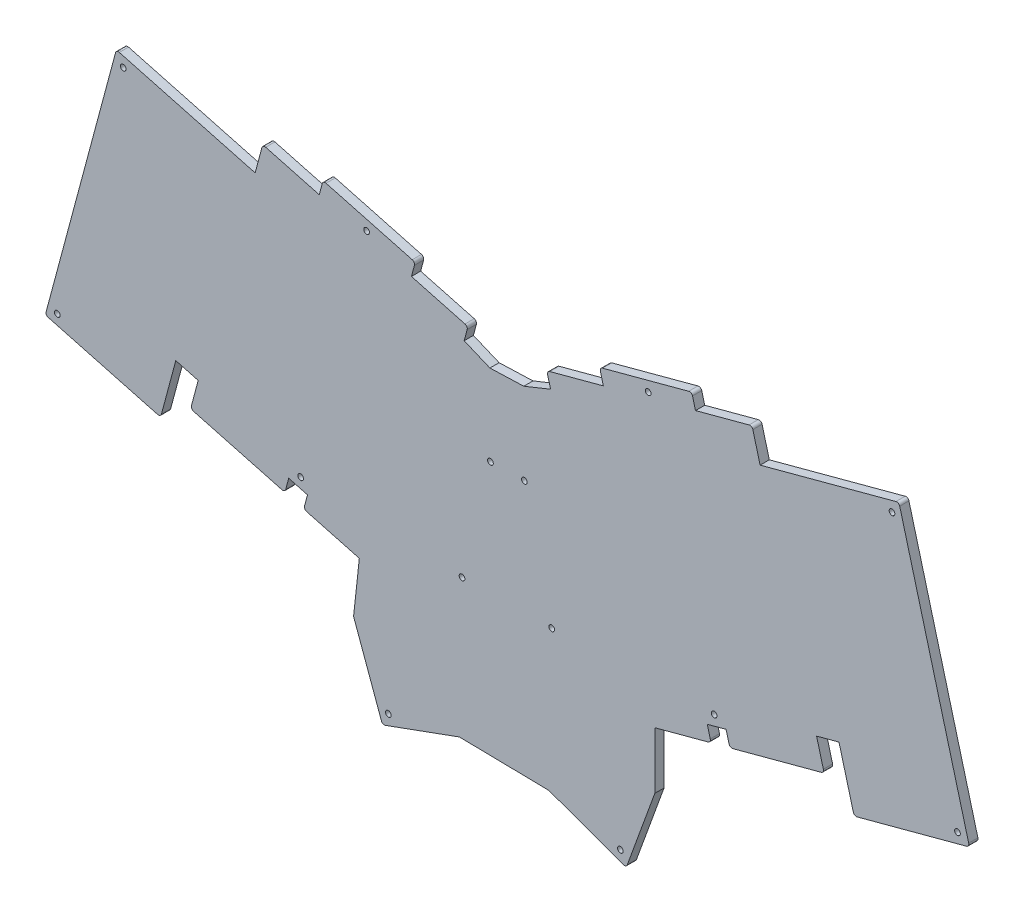
SolidWorks part; units mm, degrees
ref_plane "Front Plane" through (0, 0, 0) normal (0, 0, 1) x (1, 0, 0)
ref_plane "Top Plane" through (0, 0, 0) normal (0, 1, 0) x (1, 0, 0)
ref_plane "Right Plane" through (0, 0, 0) normal (1, 0, 0) x (0, 0, -1)
sketch "Model" plane through (0, 0, 0) normal (0, 0, 1) x (1, 0, 0)
  line L0 (282.165, 226.202) -> (288.4436, 227.8841) construction
  line L1 (267.373, 281.405) -> (273.6516, 283.0871) construction
  line L2 (195.392, 284.0785) -> (194.5766, 287.1211) construction
  line L3 (100.681, 283.685) -> (101.4961, 286.7277) construction
  line L4 (168.22, 168.742) -> (181.234, 164.006) construction
  line L5 (181.234, 164.006) -> (185.972, 177.021) construction
  line L6 (185.972, 177.021) -> (172.956, 181.758) construction
  line L7 (172.956, 181.758) -> (168.22, 168.742) construction
  line L8 (132.176, 184.752) -> (133.281, 181.717) construction
  line L9 (133.281, 181.717) -> (131.706, 181.144) construction
  line L10 (131.706, 181.144) -> (130.099, 185.56) construction
  line L11 (130.099, 185.56) -> (117.085, 180.823) construction
  line L12 (117.085, 180.823) -> (118.692, 176.407) construction
  line L13 (118.692, 176.407) -> (117.118, 175.834) construction
  line L14 (117.118, 175.834) -> (116.013, 178.869) construction
  line L15 (116.013, 178.869) -> (109.812, 176.612) construction
  line L16 (109.812, 176.612) -> (110.917, 173.576) construction
  line L17 (110.917, 173.576) -> (110.141, 173.294) construction
  line L18 (110.141, 173.294) -> (111.048, 170.804) construction
  line L19 (111.048, 170.804) -> (111.822, 171.086) construction
  line L20 (111.822, 171.086) -> (113.968, 165.194) construction
  line L21 (113.968, 165.194) -> (115.588, 165.784) construction
  line L22 (115.588, 165.784) -> (115.999, 164.656) construction
  line L23 (115.999, 164.656) -> (118.959, 165.734) construction
  line L24 (118.959, 165.734) -> (118.549, 166.861) construction
  line L25 (118.549, 166.861) -> (120.169, 167.452) construction
  line L26 (120.169, 167.452) -> (118.641, 171.651) construction
  line L27 (118.641, 171.651) -> (120.215, 172.224) construction
  line L28 (120.215, 172.224) -> (121.821, 167.809) construction
  line L29 (121.821, 167.809) -> (134.837, 172.545) construction
  line L30 (134.837, 172.545) -> (133.23, 176.962) construction
  line L31 (133.23, 176.962) -> (134.804, 177.535) construction
  line L32 (134.804, 177.535) -> (136.332, 173.335) construction
  line L33 (136.332, 173.335) -> (137.953, 173.925) construction
  line L34 (137.953, 173.925) -> (138.363, 172.796) construction
  line L35 (138.363, 172.796) -> (141.323, 173.874) construction
  line L36 (141.323, 173.874) -> (140.913, 175.001) construction
  line L37 (140.913, 175.001) -> (142.533, 175.592) construction
  line L38 (142.533, 175.592) -> (140.389, 181.483) construction
  line L39 (140.389, 181.483) -> (141.165, 181.766) construction
  line L40 (141.165, 181.766) -> (140.258, 184.256) construction
  line L41 (140.258, 184.256) -> (139.484, 183.974) construction
  line L42 (139.484, 183.974) -> (138.378, 187.009) construction
  line L43 (138.378, 187.009) -> (132.176, 184.752) construction
  line L44 (150.319, 175.258) -> (163.333, 170.521) construction
  line L45 (163.333, 170.521) -> (168.071, 183.535) construction
  line L46 (168.071, 183.535) -> (155.055, 188.273) construction
  line L47 (155.055, 188.273) -> (150.319, 175.258) construction
  line L48 (109.952, 197.835) -> (123.33, 194.251) construction
  line L49 (123.33, 194.251) -> (126.916, 207.629) construction
  line L50 (126.916, 207.629) -> (113.537, 211.213) construction
  line L51 (113.537, 211.213) -> (109.952, 197.835) construction
  line L52 (169.157, 208.022) -> (172.741, 194.644) construction
  line L53 (172.741, 194.644) -> (186.119, 198.228) construction
  line L54 (186.119, 198.228) -> (182.535, 211.607) construction
  line L55 (182.535, 211.607) -> (169.157, 208.022) construction
  line L56 (92.7848, 207.366) -> (106.163, 203.781) construction
  line L57 (106.163, 203.781) -> (109.747, 217.159) construction
  line L58 (109.747, 217.159) -> (96.369, 220.744) construction
  line L59 (96.369, 220.744) -> (92.7848, 207.366) construction
  line L60 (186.326, 217.552) -> (189.91, 204.174) construction
  line L61 (189.91, 204.174) -> (203.288, 207.759) construction
  line L62 (203.288, 207.759) -> (199.704, 221.137) construction
  line L63 (199.704, 221.137) -> (186.326, 217.552) construction
  line L64 (114.883, 216.236) -> (128.261, 212.652) construction
  line L65 (128.261, 212.652) -> (131.845, 226.03) construction
  line L66 (131.845, 226.03) -> (118.467, 229.614) construction
  line L67 (118.467, 229.614) -> (114.883, 216.236) construction
  line L68 (164.226, 226.423) -> (167.812, 213.045) construction
  line L69 (167.812, 213.045) -> (181.19, 216.629) construction
  line L70 (181.19, 216.629) -> (177.604, 230.007) construction
  line L71 (177.604, 230.007) -> (164.226, 226.423) construction
  line L72 (75.6158, 216.896) -> (88.9938, 213.312) construction
  line L73 (88.9938, 213.312) -> (92.5781, 226.69) construction
  line L74 (92.5781, 226.69) -> (79.2, 230.274) construction
  line L75 (79.2, 230.274) -> (75.6158, 216.896) construction
  line L76 (55.9827, 217.227) -> (69.3607, 213.643) construction
  line L77 (69.3607, 213.643) -> (72.9449, 227.021) construction
  line L78 (72.9449, 227.021) -> (59.5672, 230.605) construction
  line L79 (59.5672, 230.605) -> (55.9827, 217.227) construction
  line L80 (203.494, 227.083) -> (207.078, 213.705) construction
  line L81 (207.078, 213.705) -> (220.457, 217.29) construction
  line L82 (220.457, 217.29) -> (216.872, 230.668) construction
  line L83 (216.872, 230.668) -> (203.494, 227.083) construction
  line L84 (223.128, 227.414) -> (226.712, 214.036) construction
  line L85 (226.712, 214.036) -> (240.09, 217.62) construction
  line L86 (240.09, 217.62) -> (236.506, 230.998) construction
  line L87 (236.506, 230.998) -> (223.128, 227.414) construction
  line L88 (12.1157, 219.121) -> (25.4937, 215.536) construction
  line L89 (25.4937, 215.536) -> (29.078, 228.914) construction
  line L90 (29.078, 228.914) -> (15.7, 232.499) construction
  line L91 (15.7, 232.499) -> (12.1157, 219.121) construction
  line L92 (266.995, 229.307) -> (270.579, 215.929) construction
  line L93 (270.579, 215.929) -> (283.957, 219.513) construction
  line L94 (283.957, 219.513) -> (280.373, 232.891) construction
  line L95 (280.373, 232.891) -> (266.995, 229.307) construction
  line L96 (97.7138, 225.767) -> (111.092, 222.183) construction
  line L97 (111.092, 222.183) -> (114.677, 235.56) construction
  line L98 (114.677, 235.56) -> (101.299, 239.145) construction
  line L99 (101.299, 239.145) -> (97.7138, 225.767) construction
  line L100 (181.394, 235.953) -> (184.98, 222.575) construction
  line L101 (184.98, 222.575) -> (198.357, 226.159) construction
  line L102 (198.357, 226.159) -> (194.773, 239.538) construction
  line L103 (194.773, 239.538) -> (181.394, 235.953) construction
  line L104 (40.0473, 231.357) -> (53.425, 227.773) construction
  line L105 (53.425, 227.773) -> (57.0096, 241.151) construction
  line L106 (57.0096, 241.151) -> (43.6316, 244.735) construction
  line L107 (43.6316, 244.735) -> (40.0473, 231.357) construction
  line L108 (239.062, 241.545) -> (242.648, 228.166) construction
  line L109 (242.648, 228.166) -> (256.024, 231.75) construction
  line L110 (256.024, 231.75) -> (252.44, 245.128) construction
  line L111 (252.44, 245.128) -> (239.062, 241.545) construction
  line L112 (119.814, 234.637) -> (133.192, 231.053) construction
  line L113 (133.192, 231.053) -> (136.776, 244.431) construction
  line L114 (136.776, 244.431) -> (123.396, 248.015) construction
  line L115 (123.396, 248.015) -> (119.814, 234.637) construction
  line L116 (159.297, 244.824) -> (162.88, 231.445) construction
  line L117 (162.88, 231.445) -> (176.258, 235.03) construction
  line L118 (176.258, 235.03) -> (172.675, 248.408) construction
  line L119 (172.675, 248.408) -> (159.297, 244.824) construction
  line L120 (80.5462, 235.297) -> (93.9243, 231.713) construction
  line L121 (93.9243, 231.713) -> (97.5099, 245.091) construction
  line L122 (97.5099, 245.091) -> (84.1304, 248.675) construction
  line L123 (84.1304, 248.675) -> (80.5462, 235.297) construction
  line L124 (60.912, 235.628) -> (74.2901, 232.044) construction
  line L125 (74.2901, 232.044) -> (77.8757, 245.422) construction
  line L126 (77.8757, 245.422) -> (64.4977, 249.006) construction
  line L127 (64.4977, 249.006) -> (60.912, 235.628) construction
  line L128 (198.563, 245.484) -> (202.147, 232.106) construction
  line L129 (202.147, 232.106) -> (215.525, 235.692) construction
  line L130 (215.525, 235.692) -> (211.941, 249.069) construction
  line L131 (211.941, 249.069) -> (198.563, 245.484) construction
  line L132 (218.196, 245.814) -> (221.782, 232.436) construction
  line L133 (221.782, 232.436) -> (235.16, 236.021) construction
  line L134 (235.16, 236.021) -> (231.574, 249.399) construction
  line L135 (231.574, 249.399) -> (218.196, 245.814) construction
  line L136 (17.045, 237.521) -> (30.423, 233.937) construction
  line L137 (30.423, 233.937) -> (34.0086, 247.315) construction
  line L138 (34.0086, 247.315) -> (20.6306, 250.899) construction
  line L139 (20.6306, 250.899) -> (17.045, 237.521) construction
  line L140 (262.063, 247.708) -> (265.649, 234.33) construction
  line L141 (265.649, 234.33) -> (279.026, 237.914) construction
  line L142 (279.026, 237.914) -> (275.442, 251.292) construction
  line L143 (275.442, 251.292) -> (262.063, 247.708) construction
  line L144 (102.646, 244.168) -> (116.024, 240.584) construction
  line L145 (116.024, 240.584) -> (119.607, 253.962) construction
  line L146 (119.607, 253.962) -> (106.229, 257.546) construction
  line L147 (106.229, 257.546) -> (102.646, 244.168) construction
  line L148 (176.465, 254.354) -> (180.049, 240.976) construction
  line L149 (180.049, 240.976) -> (193.427, 244.56) construction
  line L150 (193.427, 244.56) -> (189.843, 257.938) construction
  line L151 (189.843, 257.938) -> (176.465, 254.354) construction
  line L152 (44.9778, 249.759) -> (58.3558, 246.174) construction
  line L153 (58.3558, 246.174) -> (61.94, 259.553) construction
  line L154 (61.94, 259.553) -> (48.562, 263.136) construction
  line L155 (48.562, 263.136) -> (44.9778, 249.759) construction
  line L156 (234.133, 259.945) -> (237.717, 246.567) construction
  line L157 (237.717, 246.567) -> (251.095, 250.151) construction
  line L158 (251.095, 250.151) -> (247.511, 263.529) construction
  line L159 (247.511, 263.529) -> (234.133, 259.945) construction
  line L160 (124.743, 253.038) -> (138.122, 249.454) construction
  line L161 (138.122, 249.454) -> (141.707, 262.832) construction
  line L162 (141.707, 262.832) -> (128.329, 266.416) construction
  line L163 (128.329, 266.416) -> (124.743, 253.038) construction
  line L164 (154.365, 263.224) -> (157.951, 249.845) construction
  line L165 (157.951, 249.845) -> (171.329, 253.432) construction
  line L166 (171.329, 253.432) -> (167.743, 266.809) construction
  line L167 (167.743, 266.809) -> (154.365, 263.224) construction
  line L168 (85.477, 253.699) -> (98.855, 250.114) construction
  line L169 (98.855, 250.114) -> (102.439, 263.492) construction
  line L170 (102.439, 263.492) -> (89.0612, 267.076) construction
  line L171 (89.0612, 267.076) -> (85.477, 253.699) construction
  line L172 (65.8442, 254.03) -> (79.2219, 250.443) construction
  line L173 (79.2219, 250.443) -> (82.8065, 263.823) construction
  line L174 (82.8065, 263.823) -> (69.427, 267.407) construction
  line L175 (69.427, 267.407) -> (65.8442, 254.03) construction
  line L176 (193.632, 263.885) -> (197.218, 250.507) construction
  line L177 (197.218, 250.507) -> (210.596, 254.092) construction
  line L178 (210.596, 254.092) -> (207.01, 267.47) construction
  line L179 (207.01, 267.47) -> (193.632, 263.885) construction
  line L180 (213.267, 264.215) -> (216.851, 250.837) construction
  line L181 (216.851, 250.837) -> (230.229, 254.422) construction
  line L182 (230.229, 254.422) -> (226.645, 267.8) construction
  line L183 (226.645, 267.8) -> (213.267, 264.215) construction
  line L184 (21.977, 255.922) -> (35.355, 252.338) construction
  line L185 (35.355, 252.338) -> (38.9378, 265.716) construction
  line L186 (38.9378, 265.716) -> (25.5598, 269.3) construction
  line L187 (25.5598, 269.3) -> (21.977, 255.922) construction
  line L188 (257.132, 266.109) -> (260.718, 252.729) construction
  line L189 (260.718, 252.729) -> (274.096, 256.315) construction
  line L190 (274.096, 256.315) -> (270.512, 269.693) construction
  line L191 (270.512, 269.693) -> (257.132, 266.109) construction
  line L192 (107.575, 262.569) -> (120.953, 258.984) construction
  line L193 (120.953, 258.984) -> (124.539, 272.362) construction
  line L194 (124.539, 272.362) -> (111.161, 275.947) construction
  line L195 (111.161, 275.947) -> (107.575, 262.569) construction
  line L196 (171.534, 272.755) -> (175.118, 259.377) construction
  line L197 (175.118, 259.377) -> (188.496, 262.961) construction
  line L198 (188.496, 262.961) -> (184.912, 276.339) construction
  line L199 (184.912, 276.339) -> (171.534, 272.755) construction
  line L200 (49.9071, 268.159) -> (63.2852, 264.575) construction
  line L201 (63.2852, 264.575) -> (66.8708, 277.953) construction
  line L202 (66.8708, 277.953) -> (53.4928, 281.537) construction
  line L203 (53.4928, 281.537) -> (49.9071, 268.159) construction
  line L204 (229.201, 278.346) -> (232.786, 264.968) construction
  line L205 (232.786, 264.968) -> (246.164, 268.554) construction
  line L206 (246.164, 268.554) -> (242.579, 281.932) construction
  line L207 (242.579, 281.932) -> (229.201, 278.346) construction
  line L208 (90.4074, 272.099) -> (103.785, 268.515) construction
  line L209 (103.785, 268.515) -> (107.37, 281.893) construction
  line L210 (107.37, 281.893) -> (93.992, 285.477) construction
  line L211 (93.992, 285.477) -> (90.4074, 272.099) construction
  line L212 (70.7732, 272.43) -> (84.1513, 268.844) construction
  line L213 (84.1513, 268.844) -> (87.7369, 282.222) construction
  line L214 (87.7369, 282.222) -> (74.3589, 285.808) construction
  line L215 (74.3589, 285.808) -> (70.7732, 272.43) construction
  line L216 (188.703, 282.286) -> (192.286, 268.908) construction
  line L217 (192.286, 268.908) -> (205.664, 272.493) construction
  line L218 (205.664, 272.493) -> (202.081, 285.871) construction
  line L219 (202.081, 285.871) -> (188.703, 282.286) construction
  line L220 (208.336, 282.616) -> (211.92, 269.238) construction
  line L221 (211.92, 269.238) -> (225.298, 272.822) construction
  line L222 (225.298, 272.822) -> (221.714, 286.2) construction
  line L223 (221.714, 286.2) -> (208.336, 282.616) construction
  line L224 (26.9062, 274.323) -> (40.284, 270.739) construction
  line L225 (40.284, 270.739) -> (43.8697, 284.117) construction
  line L226 (43.8697, 284.117) -> (30.4919, 287.701) construction
  line L227 (30.4919, 287.701) -> (26.9062, 274.323) construction
  line L228 (252.203, 284.508) -> (255.786, 271.131) construction
  line L229 (255.786, 271.131) -> (269.165, 274.716) construction
  line L230 (269.165, 274.716) -> (265.581, 288.094) construction
  line L231 (265.581, 288.094) -> (252.203, 284.508) construction
  line L232 (37.1808, 285.909) -> (37.996, 288.9517) construction
  line L233 (28.6991, 281.012) -> (22.4207, 282.6948) construction
  line L234 (18.8047, 217.3285) -> (17.9893, 214.2859) construction
  line L235 (13.9078, 225.81) -> (7.6293, 227.4922) construction
  line L236 (277.268, 217.721) -> (278.0831, 214.6783) construction
  line L237 (271.2033, 292.224) -> (291.0512, 218.1525) construction
  line L238 (241.3027, 224.5444) -> (243.7675, 215.3441) construction
  line L239 (81.0479, 284.015) -> (81.8635, 287.0576) construction
  line L240 (181.234, 164.006) -> (184.194, 162.9285) construction
  line L241 (91.0631, 284.5916) -> (72.6639, 289.5236) construction
  line L242 (117.85, 274.1545) -> (118.6654, 277.1971) construction
  line L243 (135.018, 264.624) -> (135.8331, 267.6667) construction
  line L244 (161.054, 265.0165) -> (160.2386, 268.0591) construction
  line L245 (178.223, 274.547) -> (177.4079, 277.5897) construction
  line L246 (215.025, 284.408) -> (214.2099, 287.4507) construction
  line L247 (258.892, 286.301) -> (258.2357, 288.7493) construction
  line L248 (196.599, 205.9665) -> (197.4144, 202.9239) construction
  line L249 (92.2965, 289.1937) -> (110.6958, 284.2617) construction
  line L250 (213.7675, 215.4975) -> (214.5828, 212.4548) construction
  line L251 (233.401, 215.828) -> (234.2161, 212.7853) construction
  line L252 (62.6717, 215.435) -> (61.8566, 212.3923) construction
  line L253 (82.3048, 215.104) -> (81.4897, 212.0613) construction
  line L254 (99.4739, 205.5735) -> (98.6586, 202.5309) construction
  line L255 (35.8867, 229.2106) -> (54.7701, 224.1516) construction
  line L256 (60.1818, 279.745) -> (60.9969, 282.7877) construction
  line L257 (72.6639, 289.5236) -> (70.1982, 280.3232) construction
  line L258 (105.8147, 195.273) -> (104.0964, 179.4507) construction
  line L259 (52.3052, 214.9511) -> (54.7701, 224.1516) construction
  line L260 (260.1862, 229.6041) -> (265.1156, 211.2042) construction
  line L261 (203.777, 289.5866) -> (185.3762, 284.6556) construction
  line L262 (30.9571, 210.8115) -> (35.8867, 229.2106) construction
  line L263 (141.707, 262.832) -> (142.5224, 265.8746) construction
  line L264 (154.365, 263.224) -> (153.5495, 266.2666) construction
  line L265 (181.234, 164.006) -> (180.1565, 161.046) construction
  line L266 (92.2965, 289.1937) -> (91.0631, 284.5916) construction
  line L267 (169.4396, 270.5248) -> (150.6904, 265.5004) construction
  line L268 (110.6958, 284.2617) -> (109.4634, 279.6637) construction
  line L269 (127.8626, 274.7318) -> (126.6303, 270.1341) construction
  line L270 (127.8626, 274.7318) -> (109.4634, 279.6637) construction
  line L271 (260.1862, 229.6041) -> (241.3027, 224.5444) construction
  line L272 (126.6303, 270.1341) -> (145.3813, 265.1084) construction
  line L273 (185.3762, 284.6556) -> (186.6084, 280.0546) construction
  line L274 (142.3447, 270.8715) -> (153.3719, 271.2634)
  line L275 (203.777, 289.5866) -> (205.0099, 284.986) construction
  line L276 (168.2073, 275.1248) -> (169.4396, 270.5248) construction
  line L277 (205.0099, 284.986) -> (223.4098, 289.9154) construction
  line L278 (223.4098, 289.9154) -> (226.0339, 280.1206) construction
  line L279 (186.6084, 280.0546) -> (168.2073, 275.1248) construction
  line L280 (104.0964, 179.4507) -> (110.9864, 160.5147) construction
  line L281 (152.687, 181.7655) -> (183.603, 170.5135) construction
  line L282 (110.5015, 171.0598) -> (141.4185, 182.3092) construction
  line L283 (27.2858, 222.225) -> (33.5644, 220.5428) construction
  line L284 (90.3394, 209.6904) -> (72.6399, 214.4322) construction
  line L285 (71.4079, 209.8335) -> (72.6399, 214.4322) construction
  line L286 (89.1069, 205.0898) -> (90.3394, 209.6904) construction
  line L287 (89.1069, 205.0898) -> (107.1497, 200.256) construction
  line L288 (107.1497, 200.256) -> (105.8147, 195.273) construction
  line L289 (110.9864, 160.5147) -> (131.4289, 167.9529) construction
  line L290 (71.4079, 209.8335) -> (52.3052, 214.9511) construction
  line L291 (5.0216, 217.7602) -> (25.0282, 292.4264) construction
  line L292 (130.099, 185.56) -> (121.821, 167.809) construction
  line L293 (190.0384, 195.7708) -> (190.0096, 178.9037) construction
  line L294 (235.89, 280.139) -> (235.2337, 282.5873) construction
  line L295 (162.6744, 167.408) -> (183.1165, 159.9688) construction
  line L296 (131.4289, 167.9529) -> (162.6744, 167.408) construction
  line L297 (5.0216, 217.7602) -> (30.9571, 210.8115) construction
  line L298 (46.7361, 229.565) -> (45.921, 226.5223) construction
  line L299 (265.1156, 211.2042) -> (291.0512, 218.1525) construction
  line L300 (25.0282, 292.4264) -> (70.1982, 280.3232) construction
  line L301 (226.0339, 280.1206) -> (258.2357, 288.7493) construction
  line L302 (258.2357, 288.7493) -> (271.2033, 292.224) construction
  line L303 (128.329, 170.177) -> (129.4061, 167.2169) construction
  line L304 (249.336, 229.958) -> (250.1513, 226.9153) construction
  line L305 (268.787, 222.618) -> (262.5084, 220.9359) construction
  line L306 (109.952, 197.835) -> (106.7322, 198.6976) construction
  line L307 (-2.3268, 213.5174) -> (20.7855, 299.7748)
  line L308 (186.119, 198.228) -> (189.1617, 199.0431) construction
  line L309 (206.9661, 205.4835) -> (188.7445, 200.6005) construction
  line L310 (188.7445, 200.6005) -> (190.0384, 195.7708) construction
  line L311 (20.7855, 299.7748) -> (65.9558, 287.6716)
  line L312 (68.4216, 296.8725) -> (65.9558, 287.6716)
  line L313 (86.821, 291.9405) -> (68.4216, 296.8725)
  line L314 (88.0544, 296.5426) -> (86.821, 291.9405)
  line L315 (88.0544, 296.5426) -> (118.0445, 288.5037)
  line L316 (118.0445, 288.5037) -> (116.8121, 283.9057)
  line L317 (135.2113, 278.9738) -> (116.8121, 283.9057)
  line L318 (135.2113, 278.9738) -> (133.9791, 274.3762)
  line L319 (133.9791, 274.3762) -> (142.3447, 270.8715)
  line L320 (153.3719, 271.2634) -> (162.0915, 274.7674)
  line L321 (20.7855, 299.7748) -> (25.0282, 292.4264) construction
  line L322 (160.859, 279.3678) -> (162.0915, 274.7674)
  line L323 (179.2607, 284.2977) -> (160.859, 279.3678)
  line L324 (178.0286, 288.8984) -> (179.2607, 284.2977)
  line L325 (208.0195, 296.9352) -> (178.0286, 288.8984)
  line L326 (208.0195, 296.9352) -> (209.2525, 292.3342)
  line L327 (209.2525, 292.3342) -> (227.6528, 297.2637)
  line L328 (227.6528, 297.2637) -> (230.2767, 287.4692)
  line L329 (230.2767, 287.4692) -> (275.4459, 299.5725)
  line L330 (298.3998, 213.9096) -> (294.5027, 216.1597) construction
  line L331 (275.4459, 299.5725) -> (298.3998, 213.9096)
  line L332 (260.8726, 203.856) -> (298.3998, 213.9096)
  line L333 (255.9433, 222.2556) -> (260.8726, 203.856)
  line L334 (255.9433, 222.2556) -> (248.6509, 220.3017)
  line L335 (183.1165, 159.9688) -> (190.0096, 178.9037) construction
  line L336 (248.6509, 220.3017) -> (251.1158, 211.1012)
  line L337 (220.4222, 202.8783) -> (251.1158, 211.1012)
  line L338 (219.1898, 207.4775) -> (220.4222, 202.8783)
  line L339 (213.082, 205.8412) -> (219.1898, 207.4775)
  line L340 (206.9661, 205.4835) -> (205.7333, 210.084) construction
  line L341 (223.4323, 214.8256) -> (224.6648, 210.2265) construction
  line L342 (205.7333, 210.084) -> (223.4323, 214.8256) construction
  line L343 (214.3147, 201.2411) -> (213.082, 205.8412)
  line L344 (214.3147, 201.2411) -> (196.0393, 196.3437)
  line L345 (224.6648, 210.2265) -> (243.7675, 215.3441) construction
  line L346 (196.0393, 196.3437) -> (196.0078, 177.8406)
  line L347 (150.6904, 265.5004) -> (170.7656, 190.6076) construction
  line L348 (186.7023, 152.2789) -> (196.0078, 177.8406)
  line L349 (161.566, 161.4264) -> (186.7023, 152.2789)
  line L350 (132.4358, 161.9344) -> (161.566, 161.4264)
  line L351 (107.3996, 152.8248) -> (132.4358, 161.9344)
  line L352 (97.9807, 178.7109) -> (107.3996, 152.8248)
  line L353 (99.8582, 195.9979) -> (97.9807, 178.7109)
  line L354 (141.707, 262.832) -> (154.365, 263.224) construction
  line L355 (81.7586, 200.8468) -> (99.8582, 195.9979)
  line L356 (81.7586, 200.8468) -> (82.9911, 205.4475)
  line L357 (82.9911, 205.4475) -> (76.8829, 207.0839)
  line L358 (75.6509, 202.4852) -> (76.8829, 207.0839)
  line L359 (75.6509, 202.4852) -> (44.9569, 210.7082)
  line L360 (44.9569, 210.7082) -> (47.4218, 219.9086)
  line L361 (40.1295, 221.8623) -> (47.4218, 219.9086)
  line L362 (35.1999, 203.4631) -> (40.1295, 221.8623)
  line L363 (-2.3268, 213.5174) -> (35.1999, 203.4631)
  line L364 (20.7855, 299.7748) -> (23.0356, 295.8777) construction
  line L365 (142.5224, 265.8746) -> (153.5495, 266.2666) construction
  line L366 (275.4459, 299.5725) -> (271.2033, 292.224) construction
  line L367 (291.0512, 218.1525) -> (298.3998, 213.9096) construction
  line L368 (-2.3268, 213.5174) -> (5.0216, 217.7602) construction
  line L369 (107.3996, 152.8248) -> (110.9864, 160.5147) construction
  line L370 (183.1165, 159.9688) -> (186.7023, 152.2789) construction
  line L371 (107.3996, 152.8248) -> (109.3018, 156.903) construction
  line L372 (184.8006, 156.3573) -> (186.7023, 152.2789) construction
  line L373 (106.163, 203.781) -> (189.91, 204.174) construction
  line L374 (101.4961, 286.7277) -> (103.0495, 292.5232) construction
  line L375 (194.5766, 287.1211) -> (193.0241, 292.9168) construction
  line L376 (23.0356, 295.8777) -> (23.8591, 298.9513) construction
  line L377 (193.0241, 292.9168) -> (193.8474, 289.8432) construction
  line L378 (214.5828, 212.4548) -> (216.1359, 206.6593) construction
  line L379 (103.0495, 292.5232) -> (102.2257, 289.4497) construction
  line L380 (275.4459, 299.5725) -> (273.1959, 295.6754) construction
  line L381 (-2.3268, 213.5174) -> (1.5702, 215.7675) construction
  line L382 (81.4897, 212.0613) -> (79.937, 206.2657) construction
  line L383 (81.4897, 212.0613) -> (79.937, 206.2657) construction
  line L384 (214.5828, 212.4548) -> (216.1359, 206.6593) construction
  line L385 (145.3813, 265.1084) -> (125.265, 190.0622) construction
  line L386 (190.0384, 195.7708) -> (170.7656, 190.6076) construction
  line L387 (148.0359, 266.0706) -> (148.0365, 203.9775) construction
  line L388 (105.8147, 195.273) -> (125.265, 190.0622) construction
  line L389 (104.0964, 179.4507) -> (140.9309, 192.8582) construction
  line L390 (190.0096, 178.9037) -> (153.1726, 192.3111) construction
  line L391 (152.687, 181.7655) -> (149.727, 182.8428) construction
  line L392 (162.6744, 167.408) -> (146.281, 173.3738) construction
  line L393 (153.1726, 192.3111) -> (146.281, 173.3738) construction
  line L394 (131.4289, 167.9529) -> (147.823, 173.9234) construction
  line L395 (141.4185, 182.3092) -> (144.3786, 183.3863) construction
  line L396 (140.9309, 192.8582) -> (147.823, 173.9234) construction
  line L397 (110.5015, 171.0598) -> (107.5414, 169.9827) construction
  line L398 (123.592, 183.1915) -> (122.5136, 186.1545) construction
  line L399 (105.8147, 195.273) -> (183.187, 229.264) construction
  line L400 (171.073, 185.7954) -> (164.1828, 166.8591) construction
  line L401 (112.8845, 228.8715) -> (190.0384, 195.7708) construction
  line L402 (105.8147, 195.273) -> (133.2811, 207.3395) construction
  line L403 (162.4685, 207.5989) -> (190.0384, 195.7708) construction
  line L404 (136.776, 244.431) -> (159.297, 244.824) construction
  line L405 (136.776, 244.431) -> (142.5224, 244.5313) construction
  line L406 (159.297, 244.824) -> (153.5495, 244.7237) construction
  line L407 (79.937, 206.2657) -> (80.7604, 209.3393) construction
  line L408 (216.1359, 206.6593) -> (215.3122, 209.7329) construction
  line L425 (164.1828, 166.8591) -> (183.1165, 159.9688) construction
  line L426 (190.0096, 178.9037) -> (171.073, 185.7954) construction
  line L427 (99.8582, 195.9979) -> (99.8582, 195.9979) construction
  line L428 (99.8582, 195.9979) -> (97.9807, 178.7109) construction
  line L429 (150.6904, 265.5004) -> (145.3813, 265.1084) construction
  line L430 (149.6841, 271.4425) -> (145.9529, 271.1669) construction
  line L431 (133.9791, 274.3762) -> (145.9529, 271.1669) construction
  line L432 (162.0915, 274.7674) -> (149.6841, 271.4425) construction
  line L433 (256.6828, 294.5448) -> (275.4459, 299.5725) construction
  line L434 (230.2767, 287.4692) -> (256.6828, 294.5448) construction
  line L435 (196.0393, 196.3437) -> (196.0393, 196.3437) construction
  line L436 (196.0393, 196.3437) -> (196.0078, 177.8406) construction
  circle A0 centre (23.0356, 295.8777) radius 0.925
  circle A1 centre (109.3018, 156.903) radius 0.925
  circle A2 centre (184.8006, 156.3573) radius 0.925
  circle A3 centre (193.8474, 289.8432) radius 0.925
  circle A4 centre (102.2257, 289.4497) radius 0.925
  circle A5 centre (273.1959, 295.6754) radius 0.925
  circle A6 centre (1.5702, 215.7675) radius 0.925
  circle A7 centre (294.5027, 216.1597) radius 0.925
  circle A8 centre (80.7604, 209.3393) radius 0.925
  circle A9 centre (215.3122, 209.7329) radius 0.925
  circle A10 centre (133.2811, 207.3395) radius 0.925
  circle A11 centre (162.4685, 207.5989) radius 0.925
  circle A12 centre (142.5224, 244.5313) radius 0.925
  circle A13 centre (153.5495, 244.7237) radius 0.925
  point P253 (61.8566, 212.3923)
  point P289 (81.8635, 287.0576)
  point P293 (194.5766, 287.1211)
  point P295 (101.4961, 286.7277)
  point P297 (81.4897, 212.0613)
  point P361 (125.96, 176.6845)
  point P362 (125.96, 176.6845)
  point P374 (214.5828, 212.4548)
  point P377 (234.2161, 212.7853)
  point P378 (177.4079, 277.5897)
  point P386 (214.2099, 287.4507)
  dimension "D5" = 6
  dimension "D4" = 1.85
  dimension "D7" = 30.011
  dimension "D8" = 30
  dimension "D1" = 9.5249
  dimension "D2" = 6.5
  dimension "D3" = 5
  dimension "D6" = 4.5
extrude "Boss-Extrude1" add sketch "Model" along normal blind 3
fillet "Fillet1" radius 1 22 edges at (-2.3268, 213.5174, 1.5) (75.6509, 202.4852, 1.5) (44.9569, 210.7082, 1.5) (81.7586, 200.8468, 1.5) (35.1999, 203.4631, 1.5) (107.3996, 152.8248, 1.5) (186.7023, 152.2789, 1.5) (214.3147, 201.2411, 1.5) (220.4222, 202.8783, 1.5) (251.1158, 211.1012, 1.5) (260.8726, 203.856, 1.5) (298.3998, 213.9096, 1.5) (275.4459, 299.5725, 1.5) (227.6528, 297.2637, 1.5) (208.0195, 296.9352, 1.5) (178.0286, 288.8984, 1.5) (160.859, 279.3678, 1.5) (135.2113, 278.9738, 1.5) (118.0445, 288.5037, 1.5) (88.0544, 296.5426, 1.5) (68.4216, 296.8725, 1.5) (20.7855, 299.7748, 1.5)
